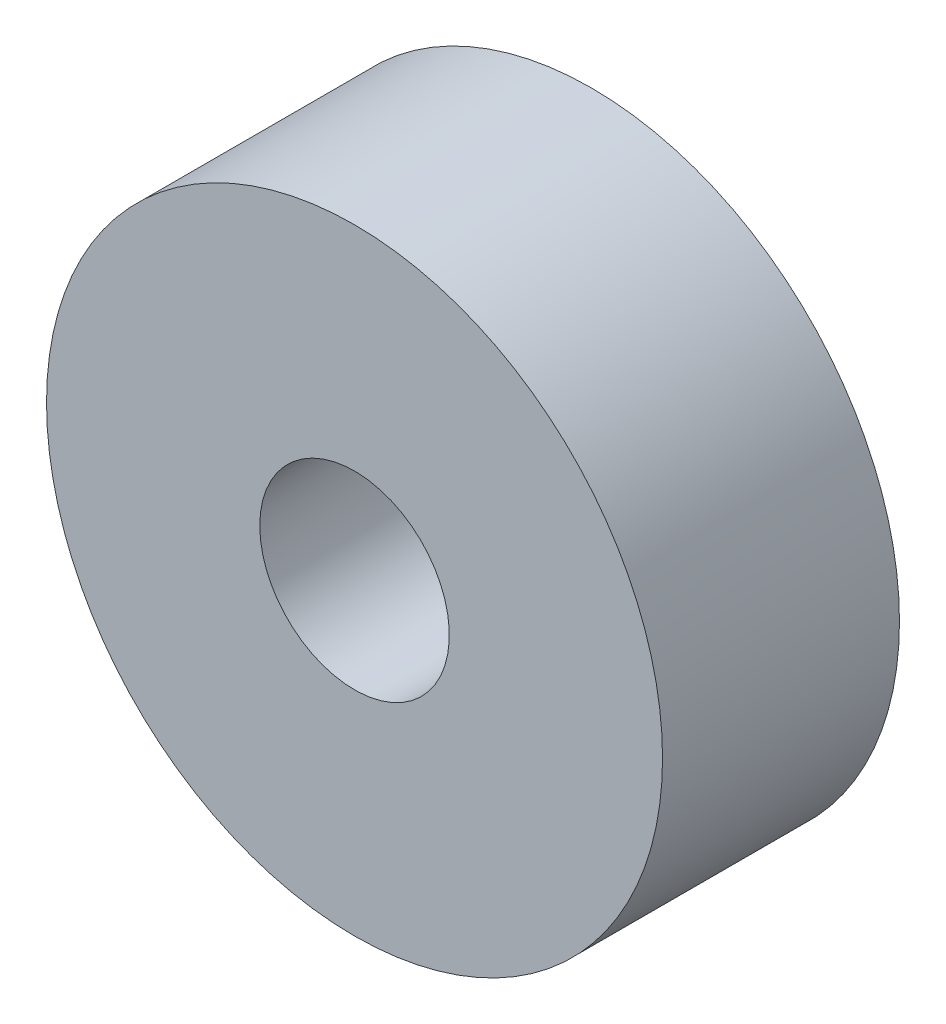
SolidWorks part; units mm, degrees
ref_plane "Plan de face" through (0, 0, 0) normal (0, 0, 1) x (1, 0, 0)
ref_plane "Plan de dessus" through (0, 0, 0) normal (0, 1, 0) x (1, 0, 0)
ref_plane "Plan de droite" through (0, 0, 0) normal (1, 0, 0) x (0, 0, -1)
sketch "Esquisse1" plane through (0, 0, 0) normal (0, 0, 1) x (1, 0, 0)
  circle A0 centre (0, 0) radius 6.5
  dimension "D1" = 13
extrude "Boss.-Extru.1" add sketch "Esquisse1" along normal blind 5
sketch "Esquisse2" plane through (0, 0, 0) normal (0, 0, -1) x (-1, 0, 0)
  circle A0 centre (0, 0) radius 2
extrude "Enlèv. mat.-Extru.1" cut sketch "Esquisse2" against normal blind 5
